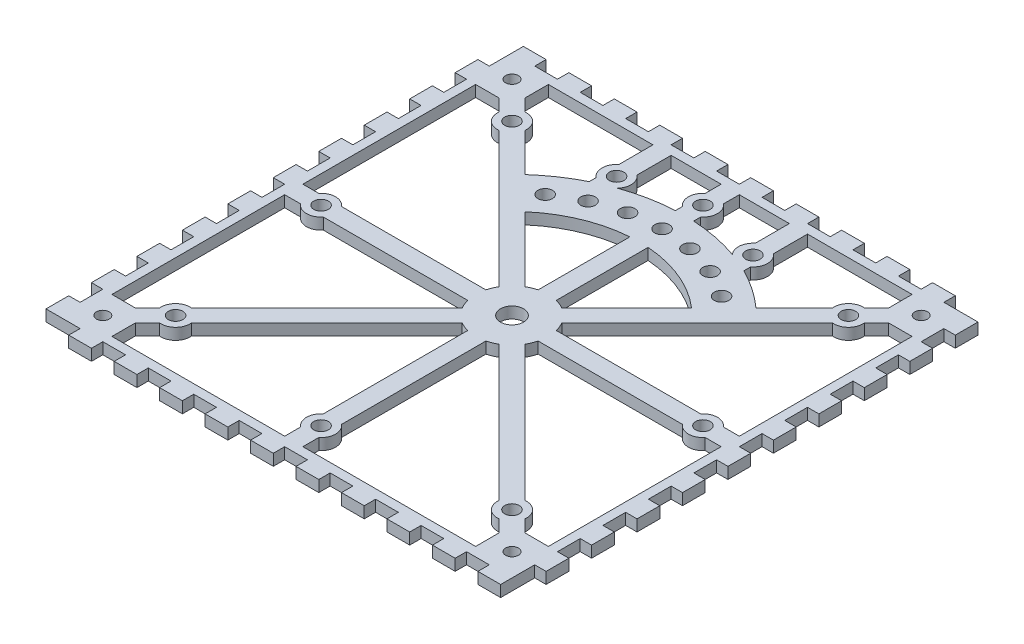
SolidWorks part; units mm, degrees
ref_plane "Front Plane" through (0, 0, 0) normal (0, 0, 1) x (1, 0, 0)
ref_plane "Top Plane" through (0, 0, 0) normal (0, 1, 0) x (1, 0, 0)
ref_plane "Right Plane" through (0, 0, 0) normal (1, 0, 0) x (0, 0, -1)
sketch "Sketch1" plane through (0, 0, 0) normal (0, 1, 0) x (1, 0, 0)
  line L449 (-50, 50) -> (-50, 52.5)
  line L480 (-40, 48) -> (-17, 48)
  line L481 (-48, 40) -> (-48, 2)
  line L483 (-40, -48) -> (-2, -48)
  line L484 (48, 40) -> (48, 2)
  line L486 (48, 2) -> (44.498, 2)
  line L487 (48, -2) -> (48, -40)
  line L488 (40, -42.8284) -> (37.3521, -40.1806)
  line L489 (48, -2) -> (44.498, -2)
  line L490 (-2, -48) -> (-2, -44.498)
  line L491 (2, -48) -> (40, -48)
  line L494 (-40, -42.8284) -> (-37.3521, -40.1806)
  line L496 (-48, -2) -> (-44.498, -2)
  line L497 (-48, 2) -> (-44.498, 2)
  line L498 (-40, 42.8284) -> (-37.3521, 40.1806)
  line L499 (2, 48) -> (2, 44.498)
  line L500 (-33.8194, 36.6479) -> (-25.4186, 28.247)
  line L501 (-36.6479, 33.8194) -> (-6.8914, 4.063)
  line L502 (-2, 39.502) -> (-2, 37.9473)
  line L503 (2, 39.502) -> (2, 37.9473)
  line L504 (33.8194, 36.6479) -> (25.4186, 28.247)
  line L505 (36.6479, 33.8194) -> (6.8914, 4.063)
  line L506 (39.502, 2) -> (7.746, 2)
  line L507 (39.502, -2) -> (7.746, -2)
  line L508 (33.8194, -36.6479) -> (4.063, -6.8914)
  line L509 (36.6479, -33.8194) -> (6.8914, -4.063)
  line L510 (-2, -39.502) -> (-2, -7.746)
  line L511 (2, -39.502) -> (2, -7.746)
  line L513 (-33.8194, -36.6479) -> (-4.063, -6.8914)
  line L514 (-39.502, 2) -> (-7.746, 2)
  line L515 (-39.502, -2) -> (-7.746, -2)
  line L516 (-48, -2) -> (-48, -40)
  line L517 (-42.8284, 40) -> (-40.1806, 37.3521)
  line L518 (-50, 52.5) -> (-45, 52.5)
  line L519 (-45, 52.5) -> (-45, 50)
  line L520 (2, 48) -> (13, 48)
  line L521 (-2, 48) -> (-2, 44.498)
  line L522 (40, 42.8284) -> (37.3521, 40.1806)
  line L523 (42.8284, 40) -> (40.1806, 37.3521)
  line L524 (-45, 50) -> (-40, 50)
  line L525 (-40, 50) -> (-40, 52.5)
  line L526 (-40, 52.5) -> (-35, 52.5)
  line L527 (42.8284, -40) -> (40.1806, -37.3521)
  line L528 (-35, 52.5) -> (-35, 50)
  line L529 (-35, 50) -> (-30, 50)
  line L530 (2, -48) -> (2, -44.498)
  line L531 (-42.8284, -40) -> (-40.1806, -37.3521)
  line L532 (-30, 50) -> (-30, 52.5)
  line L546 (-30, 52.5) -> (-25, 52.5)
  line L547 (-25, 52.5) -> (-25, 50)
  line L548 (-25, 50) -> (-20, 50)
  line L549 (-20, 50) -> (-20, 52.5)
  line L550 (-20, 52.5) -> (-15, 52.5)
  line L551 (-15, 52.5) -> (-15, 50)
  line L552 (-15, 50) -> (-10, 50)
  line L553 (-10, 50) -> (-10, 52.5)
  line L554 (-10, 52.5) -> (-5, 52.5)
  line L555 (-5, 52.5) -> (-5, 50)
  line L556 (-5, 50) -> (0, 50)
  line L557 (0, 50) -> (0, 52.5)
  line L558 (0, 52.5) -> (5, 52.5)
  line L559 (5, 52.5) -> (5, 50)
  line L560 (5, 50) -> (10, 50)
  line L561 (10, 50) -> (10, 52.5)
  line L562 (10, 52.5) -> (15, 52.5)
  line L563 (15, 52.5) -> (15, 50)
  line L564 (15, 50) -> (20, 50)
  line L565 (20, 50) -> (20, 52.5)
  line L566 (20, 52.5) -> (25, 52.5)
  line L567 (25, 52.5) -> (25, 50)
  line L568 (25, 50) -> (30, 50)
  line L569 (30, 50) -> (30, 52.5)
  line L570 (30, 52.5) -> (35, 52.5)
  line L571 (35, 52.5) -> (35, 50)
  line L572 (35, 50) -> (40, 50)
  line L573 (40, 50) -> (40, 52.5)
  line L574 (40, 52.5) -> (45, 52.5)
  line L575 (45, 52.5) -> (45, 50)
  line L576 (45, 50) -> (50, 50)
  line L577 (50, 50) -> (52.5, 50)
  line L578 (52.5, 50) -> (52.5, 45)
  line L579 (52.5, 45) -> (50, 45)
  line L580 (50, 45) -> (50, 40)
  line L582 (50, 40) -> (52.5, 40)
  line L583 (52.5, 40) -> (52.5, 35)
  line L584 (52.5, 35) -> (50, 35)
  line L585 (50, 35) -> (50, 30)
  line L586 (50, 30) -> (52.5, 30)
  line L587 (52.5, 30) -> (52.5, 25)
  line L588 (52.5, 25) -> (50, 25)
  line L589 (50, 25) -> (50, 20)
  line L590 (50, 20) -> (52.5, 20)
  line L591 (52.5, 20) -> (52.5, 15)
  line L592 (52.5, 15) -> (50, 15)
  line L593 (50, 15) -> (50, 10)
  line L594 (50, 10) -> (52.5, 10)
  line L595 (52.5, 10) -> (52.5, 5)
  line L596 (52.5, 5) -> (50, 5)
  line L597 (50, 5) -> (50, 0)
  line L598 (50, 0) -> (52.5, 0)
  line L599 (52.5, 0) -> (52.5, -5)
  line L600 (52.5, -5) -> (50, -5)
  line L601 (50, -5) -> (50, -10)
  line L602 (50, -10) -> (52.5, -10)
  line L603 (52.5, -10) -> (52.5, -15)
  line L604 (52.5, -15) -> (50, -15)
  line L605 (50, -15) -> (50, -20)
  line L606 (50, -20) -> (52.5, -20)
  line L607 (52.5, -20) -> (52.5, -25)
  line L608 (52.5, -25) -> (50, -25)
  line L609 (50, -25) -> (50, -30)
  line L610 (50, -30) -> (52.5, -30)
  line L611 (52.5, -30) -> (52.5, -35)
  line L612 (52.5, -35) -> (50, -35)
  line L613 (50, -35) -> (50, -40)
  line L614 (50, -40) -> (52.5, -40)
  line L615 (52.5, -40) -> (52.5, -45)
  line L616 (52.5, -45) -> (50, -45)
  line L617 (50, -45) -> (50, -50)
  line L618 (50, -50) -> (50, -52.5)
  line L619 (50, -52.5) -> (45, -52.5)
  line L620 (45, -52.5) -> (45, -50)
  line L621 (45, -50) -> (40, -50)
  line L623 (40, -50) -> (40, -52.5)
  line L624 (40, -52.5) -> (35, -52.5)
  line L625 (35, -52.5) -> (35, -50)
  line L626 (35, -50) -> (30, -50)
  line L627 (30, -50) -> (30, -52.5)
  line L628 (30, -52.5) -> (25, -52.5)
  line L629 (25, -52.5) -> (25, -50)
  line L630 (25, -50) -> (20, -50)
  line L631 (20, -50) -> (20, -52.5)
  line L632 (20, -52.5) -> (15, -52.5)
  line L633 (15, -52.5) -> (15, -50)
  line L634 (15, -50) -> (10, -50)
  line L635 (10, -50) -> (10, -52.5)
  line L636 (10, -52.5) -> (5, -52.5)
  line L637 (5, -52.5) -> (5, -50)
  line L638 (5, -50) -> (0, -50)
  line L639 (0, -50) -> (0, -52.5)
  line L640 (0, -52.5) -> (-5, -52.5)
  line L641 (-5, -52.5) -> (-5, -50)
  line L642 (-5, -50) -> (-10, -50)
  line L643 (-10, -50) -> (-10, -52.5)
  line L644 (-10, -52.5) -> (-15, -52.5)
  line L645 (-15, -52.5) -> (-15, -50)
  line L646 (-15, -50) -> (-20, -50)
  line L647 (-20, -50) -> (-20, -52.5)
  line L648 (-20, -52.5) -> (-25, -52.5)
  line L649 (-25, -52.5) -> (-25, -50)
  line L650 (-25, -50) -> (-30, -50)
  line L651 (-30, -50) -> (-30, -52.5)
  line L652 (-30, -52.5) -> (-35, -52.5)
  line L653 (-35, -52.5) -> (-35, -50)
  line L654 (-35, -50) -> (-40, -50)
  line L655 (-40, -50) -> (-40, -52.5)
  line L656 (-40, -52.5) -> (-45, -52.5)
  line L657 (-45, -52.5) -> (-45, -50)
  line L658 (-45, -50) -> (-50, -50)
  line L659 (-50, -50) -> (-52.5, -50)
  line L660 (-52.5, -50) -> (-52.5, -45)
  line L661 (-52.5, -45) -> (-50, -45)
  line L662 (-50, -45) -> (-50, -40)
  line L664 (-50, -40) -> (-52.5, -40)
  line L665 (-52.5, -40) -> (-52.5, -35)
  line L666 (-52.5, -35) -> (-50, -35)
  line L667 (-50, -35) -> (-50, -30)
  line L668 (-50, -30) -> (-52.5, -30)
  line L669 (-52.5, -30) -> (-52.5, -25)
  line L670 (-52.5, -25) -> (-50, -25)
  line L671 (-50, -25) -> (-50, -20)
  line L672 (-50, -20) -> (-52.5, -20)
  line L673 (-52.5, -20) -> (-52.5, -15)
  line L674 (-52.5, -15) -> (-50, -15)
  line L675 (-50, -15) -> (-50, -10)
  line L676 (-50, -10) -> (-52.5, -10)
  line L677 (-52.5, -10) -> (-52.5, -5)
  line L678 (-52.5, -5) -> (-50, -5)
  line L679 (-50, -5) -> (-50, 0)
  line L680 (-50, 0) -> (-52.5, 0)
  line L681 (-52.5, 0) -> (-52.5, 5)
  line L682 (-52.5, 5) -> (-50, 5)
  line L683 (-50, 5) -> (-50, 10)
  line L684 (-50, 10) -> (-52.5, 10)
  line L685 (-52.5, 10) -> (-52.5, 15)
  line L686 (-52.5, 15) -> (-50, 15)
  line L687 (-50, 15) -> (-50, 20)
  line L688 (-50, 20) -> (-52.5, 20)
  line L689 (-52.5, 20) -> (-52.5, 25)
  line L690 (-52.5, 25) -> (-50, 25)
  line L691 (-50, 25) -> (-50, 30)
  line L692 (-50, 30) -> (-52.5, 30)
  line L693 (-52.5, 30) -> (-52.5, 35)
  line L694 (-52.5, 35) -> (-50, 35)
  line L695 (-50, 35) -> (-50, 40)
  line L696 (-50, 40) -> (-52.5, 40)
  line L697 (-52.5, 40) -> (-52.5, 45)
  line L698 (-52.5, 45) -> (-50, 45)
  line L699 (-50, 45) -> (-50, 50)
  line L703 (-48, 40) -> (-42.8284, 40)
  line L704 (-40, 48) -> (-40, 42.8284)
  line L708 (48, 40) -> (42.8284, 40)
  line L709 (40, 48) -> (40, 42.8284)
  line L713 (48, -40) -> (42.8284, -40)
  line L714 (40, -48) -> (40, -42.8284)
  line L718 (-48, -40) -> (-42.8284, -40)
  line L719 (-40, -48) -> (-40, -42.8284)
  line L720 (-6.8914, -4.063) -> (-36.6479, -33.8194)
  line L725 (-18.3342, 21.1626) -> (-4.063, 6.8914)
  line L726 (18.3342, 21.1626) -> (4.063, 6.8914)
  line L727 (-17, 48) -> (-17, 40.498)
  line L729 (-13, 48) -> (-13, 40.498)
  line L731 (13, 48) -> (13, 40.498)
  line L733 (17, 48) -> (17, 40.498)
  line L735 (-13, 48) -> (-2, 48)
  line L736 (17, 48) -> (40, 48)
  line L737 (-2, 27.9285) -> (-2, 7.746)
  line L738 (2, 27.9285) -> (2, 7.746)
  line L739 (-17, 35.502) -> (-17, 33.9853)
  line L740 (17, 35.502) -> (17, 33.9853)
  circle A10 centre (0, 0) radius 2.55
  arc A14 (-6.8914, 4.063) -> (-7.746, 2) centre (0, 0) ccw
  arc A15 (4.063, 6.8914) -> (2, 7.746) centre (0, 0) ccw
  arc A16 (6.8914, -4.063) -> (7.746, -2) centre (0, 0) ccw
  arc A17 (-4.063, -6.8914) -> (-2, -7.746) centre (0, 0) ccw
  circle A51 centre (37, -37) radius 1.6
  circle A52 centre (-37, -37) radius 1.6
  circle A53 centre (-37, 37) radius 1.6
  circle A56 centre (37, 37) radius 1.6
  arc A73 (-7.746, -2) -> (-6.8914, -4.063) centre (0, 0) ccw
  arc A74 (-2, 7.746) -> (-4.063, 6.8914) centre (0, 0) ccw
  arc A75 (2, -7.746) -> (4.063, -6.8914) centre (0, 0) ccw
  arc A76 (7.746, 2) -> (6.8914, 4.063) centre (0, 0) ccw
  arc A85 (-40.1806, 37.3521) -> (-36.6479, 33.8194) centre (-37, 37) ccw
  arc A86 (36.6479, 33.8194) -> (40.1806, 37.3521) centre (37, 37) ccw
  arc A87 (33.8194, -36.6479) -> (37.3521, -40.1806) centre (37, -37) ccw
  circle A88 centre (0, 42) radius 1.6
  circle A89 centre (42, 0) radius 1.6
  circle A90 centre (-42, 0) radius 1.6
  circle A91 centre (0, -42) radius 1.6
  arc A92 (-44.498, -2) -> (-39.502, -2) centre (-42, 0) ccw
  arc A93 (-2, 44.498) -> (-2, 39.502) centre (0, 42) ccw
  arc A94 (39.502, -2) -> (44.498, -2) centre (42, 0) ccw
  arc A95 (-2, -39.502) -> (-2, -44.498) centre (0, -42) ccw
  arc A96 (-39.502, 2) -> (-44.498, 2) centre (-42, 0) ccw
  arc A97 (2, 39.502) -> (2, 44.498) centre (0, 42) ccw
  arc A98 (44.498, 2) -> (39.502, 2) centre (42, 0) ccw
  arc A99 (2, -44.498) -> (2, -39.502) centre (0, -42) ccw
  arc A100 (-37.3521, -40.1806) -> (-33.8194, -36.6479) centre (-37, -37) ccw
  arc A101 (-33.8194, 36.6479) -> (-37.3521, 40.1806) centre (-37, 37) ccw
  arc A102 (37.3521, 40.1806) -> (33.8194, 36.6479) centre (37, 37) ccw
  arc A103 (40.1806, -37.3521) -> (36.6479, -33.8194) centre (37, -37) ccw
  arc A104 (-36.6479, -33.8194) -> (-40.1806, -37.3521) centre (-37, -37) ccw
  circle A131 centre (-45, 45) radius 1.4
  circle A132 centre (45, 45) radius 1.4
  circle A133 centre (-45, -45) radius 1.4
  circle A134 centre (45, -45) radius 1.4
  circle A135 centre (0, 0) radius 33 construction
  arc A137 (18.3342, 21.1626) -> (2, 27.9285) centre (0, 0) ccw construction
  circle A138 centre (-15, 38) radius 1.6
  circle A139 centre (15, 38) radius 1.6
  arc A140 (18.3342, 21.1626) -> (2, 27.9285) centre (0, 0) ccw
  arc A142 (12.6437, 35.8349) -> (2, 37.9473) centre (0, 0) ccw construction
  arc A143 (12.6437, 35.8349) -> (2, 37.9473) centre (0, 0) ccw
  arc A144 (25.4186, 28.247) -> (17, 33.9853) centre (0, 0) ccw construction
  arc A145 (25.4186, 28.247) -> (17, 33.9853) centre (0, 0) ccw
  arc A146 (-17, 33.9853) -> (-25.4186, 28.247) centre (0, 0) ccw construction
  arc A147 (-17, 33.9853) -> (-25.4186, 28.247) centre (0, 0) ccw
  arc A148 (-2, 37.9473) -> (-12.6437, 35.8349) centre (0, 0) ccw construction
  arc A149 (-2, 37.9473) -> (-12.6437, 35.8349) centre (0, 0) ccw
  arc A150 (-2, 27.9285) -> (-18.3342, 21.1626) centre (0, 0) ccw construction
  arc A151 (-2, 27.9285) -> (-18.3342, 21.1626) centre (0, 0) ccw
  arc A152 (-17, 40.498) -> (-17, 35.502) centre (-15, 38) ccw
  arc A153 (13, 40.498) -> (12.6437, 35.8349) centre (15, 38) ccw
  arc A154 (-12.6437, 35.8349) -> (-13, 40.498) centre (-15, 38) ccw
  arc A155 (17, 35.502) -> (17, 40.498) centre (15, 38) ccw
  circle A156 centre (0, 33) radius 1.6
  circle A157 centre (6.8611, 32.2789) radius 1.6
  circle A158 centre (13.4223, 30.147) radius 1.6
  circle A159 centre (19.3969, 26.6976) radius 1.6
  circle A183 centre (-19.3969, 26.6976) radius 1.6
  circle A184 centre (-13.4223, 30.147) radius 1.6
  circle A185 centre (-6.8611, 32.2789) radius 1.6
  circle A186 centre (0, 0) radius 28 construction
  circle A187 centre (0, 0) radius 38 construction
  dimension "D6" = 4
  dimension "D7" = 4
  dimension "D4" = 10
  dimension "D1" = 10
  dimension "D3" = 10
  dimension "D2" = 10
extrude "Boss-Extrude1" add sketch "Sketch1" along normal blind 2.5
